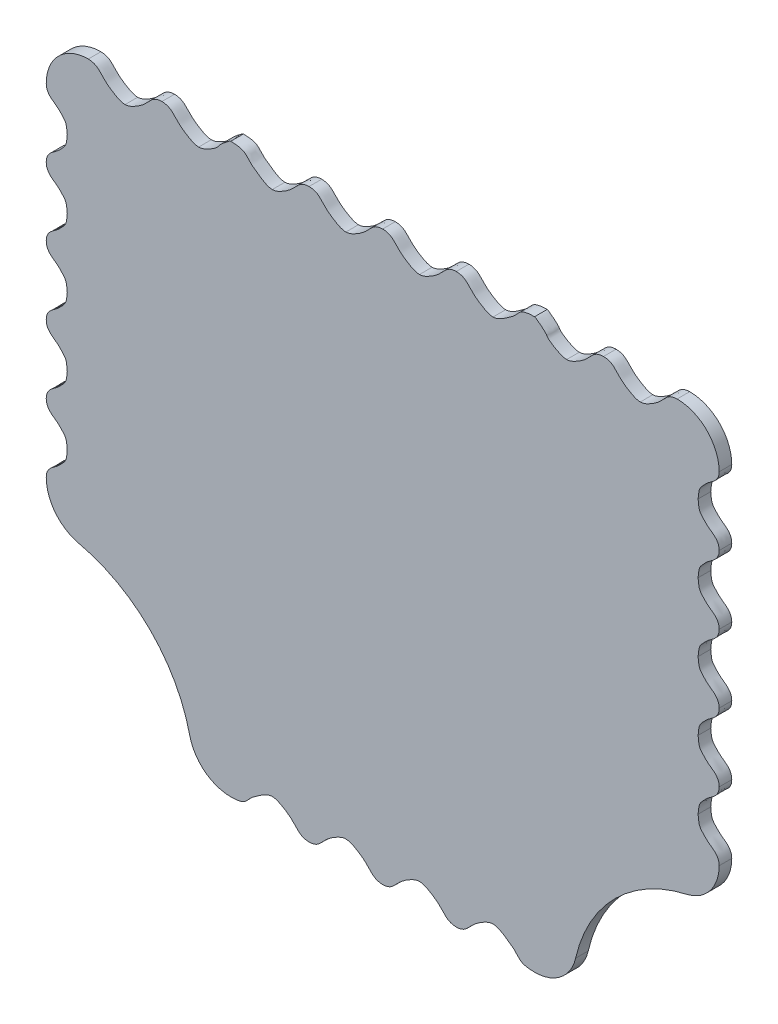
SolidWorks part; units mm, degrees
material "Beech"
ref_plane "Front" through (0, 0, 0) normal (0, 0, 1) x (1, 0, 0)
ref_plane "Top" through (0, 0, 0) normal (0, 1, 0) x (1, 0, 0)
ref_plane "Right" through (0, 0, 0) normal (1, 0, 0) x (0, 0, -1)
sketch "Sketch1" plane through (0, 0, 0) normal (0, 0, 1) x (1, 0, 0)
  line L0 (80, -32.5) -> (-80, -32.5) construction
  line L1 (-80, -67.5) -> (80, -67.5) construction
  line L2 (-80, -67.5) -> (-80, 67.5) construction
  line L3 (-80, 67.5) -> (80, 67.5) construction
  line L4 (80, -67.5) -> (80, 67.5) construction
  line L5 (-80, -67.5) -> (80, 67.5) construction
  line L6 (-80, 67.5) -> (80, -67.5) construction
  line L7 (-45, -67.5) -> (-45, 67.5) construction
  line L8 (45, -67.5) -> (45, 67.5) construction
  line L9 (80, -23.6252) -> (80, 57.5) construction
  line L10 (70, 67.5) -> (-70, 67.5) construction
  line L12 (-36.1252, -67.5) -> (36.1252, -67.5) construction
  line L13 (70, 62.5) -> (-70, 62.5) construction
  line L14 (61.25, 62.5) -> (61.25, 66.2581) construction
  line L15 (75, 57.5) -> (75, -23.6252) construction
  line L16 (0, 14.3614) -> (0, -10.6651) construction
  line L17 (75, -15.5122) -> (80, -15.5122) construction
  line L18 (-75, 57.5) -> (-75, -23.6252) construction
  line L19 (15.1664, 0) -> (-13.447, 0) construction
  arc A0 (-72.2222, -33.3751) -> (-45.8751, -59.7222) centre (-80, -67.5) cw
  arc A1 (72.2222, -33.3751) -> (45.8751, -59.7222) centre (80, -67.5) ccw
  arc A2 (-36.1252, -67.5) -> (-45.8751, -59.7222) centre (-36.1252, -57.5) cw
  arc A3 (-72.2222, -33.3751) -> (-80, -23.6252) centre (-70, -23.6252) cw
  arc A4 (45.8751, -59.7222) -> (36.1252, -67.5) centre (36.1252, -57.5) cw
  arc A5 (80, 57.5) -> (70, 67.5) centre (70, 57.5) ccw
  arc A6 (-70, 67.5) -> (-80, 57.5) centre (-70, 57.5) ccw
  arc A7 (80, -23.6252) -> (72.2222, -33.3751) centre (70, -23.6252) cw
  spline S0 degree 3 poles (70, 67.5) (68.4622, 67.4695) (66.1237, 65.2644) (66.0967, 64.9256) (62.7635, 62.457) (61.25, 62.5) knots 0 0 0 0 0.090048 0.292197 1 1 1 1
  spline S1 degree 3 poles (52.5, 67.5) (54.0378, 67.4695) (56.3763, 65.2644) (56.4033, 64.9256) (59.7365, 62.457) (61.25, 62.5) knots 0 0 0 0 0.090048 0.292197 1 1 1 1
  spline S2 degree 3 poles (52.5, 67.5) (50.9622, 67.4695) (48.6237, 65.2644) (48.5967, 64.9256) (45.2635, 62.457) (43.75, 62.5) knots 0 0 0 0 0.090048 0.292197 1 1 1 1
  spline S3 degree 3 poles (36.1252, 67.5) (36.3945, 67.4695) (39.104, 65.2644) (38.59, 64.9256) (42.2365, 62.457) (43.75, 62.5) knots 0 0 0 0 0.090048 0.292197 1 1 1 1
  spline S4 degree 3 poles (36.1252, 67.5) (33.3188, 67.4695) (31.3514, 65.2644) (30.7833, 64.9256) (27.7635, 62.457) (26.25, 62.5) knots 0 0 0 0 0.090048 0.292197 1 1 1 1
  spline S5 degree 3 poles (17.5, 67.5) (19.0378, 67.4695) (21.3763, 65.2644) (21.4033, 64.9256) (24.7365, 62.457) (26.25, 62.5) knots 0 0 0 0 0.090048 0.292197 1 1 1 1
  spline S6 degree 3 poles (17.5, 67.5) (15.9622, 67.4695) (13.6237, 65.2644) (13.5967, 64.9256) (10.2635, 62.457) (8.75, 62.5) knots 0 0 0 0 0.090048 0.292197 1 1 1 1
  spline S7 degree 3 poles (0, 67.5) (1.5378, 67.4695) (3.8763, 65.2644) (3.9033, 64.9256) (7.2365, 62.457) (8.75, 62.5) knots 0 0 0 0 0.090048 0.292197 1 1 1 1
  spline S8 degree 3 poles (0, 67.5) (-1.5378, 67.4695) (-3.8763, 65.2644) (-3.9033, 64.9256) (-7.2365, 62.457) (-8.75, 62.5) knots 0 0 0 0 0.090048 0.292197 1 1 1 1
  spline S9 degree 3 poles (-17.5, 67.5) (-15.9622, 67.4695) (-13.6237, 65.2644) (-13.5967, 64.9256) (-10.2635, 62.457) (-8.75, 62.5) knots 0 0 0 0 0.090048 0.292197 1 1 1 1
  spline S10 degree 3 poles (-17.5, 67.5) (-19.0378, 67.4695) (-21.3763, 65.2644) (-21.4033, 64.9256) (-24.7365, 62.457) (-26.25, 62.5) knots 0 0 0 0 0.090048 0.292197 1 1 1 1
  spline S11 degree 3 poles (-36.1252, 67.5) (-33.3188, 67.4695) (-31.3514, 65.2644) (-30.7833, 64.9256) (-27.7635, 62.457) (-26.25, 62.5) knots 0 0 0 0 0.090048 0.292197 1 1 1 1
  spline S12 degree 3 poles (-36.1252, 67.5) (-36.3945, 67.4695) (-39.104, 65.2644) (-38.59, 64.9256) (-42.2365, 62.457) (-43.75, 62.5) knots 0 0 0 0 0.090048 0.292197 1 1 1 1
  spline S13 degree 3 poles (-52.5, 67.5) (-50.9622, 67.4695) (-48.6237, 65.2644) (-48.5967, 64.9256) (-45.2635, 62.457) (-43.75, 62.5) knots 0 0 0 0 0.090048 0.292197 1 1 1 1
  spline S14 degree 3 poles (-52.5, 67.5) (-54.0378, 67.4695) (-56.3763, 65.2644) (-56.4033, 64.9256) (-59.7365, 62.457) (-61.25, 62.5) knots 0 0 0 0 0.090048 0.292197 1 1 1 1
  spline S15 degree 3 poles (-70, 67.5) (-68.4622, 67.4695) (-66.1237, 65.2644) (-66.0967, 64.9256) (-62.7635, 62.457) (-61.25, 62.5) knots 0 0 0 0 0.090048 0.292197 1 1 1 1
  spline S16 degree 3 poles (80, -23.6252) (80.0328, -22.0654) (78.0842, -20.4866) (77.3009, -20.0392) (75.2934, -17.9415) (75.1919, -17.7457) (75, -15.5122) knots 0 0 0 0 0.224601 0.419775 0.497315 1 1 1 1
  spline S17 degree 3 poles (80, -7.3992) (80.0328, -8.959) (78.0842, -10.5377) (77.3009, -10.9851) (75.2934, -13.0829) (75.1919, -13.2787) (75, -15.5122) knots 0 0 0 0 0.224601 0.419775 0.497315 1 1 1 1
  spline S18 degree 3 poles (80, -7.3992) (80.0328, -5.8394) (78.0842, -4.255) (77.3009, -3.8094) (75.2934, -1.7111) (75.1919, -1.5157) (75, 0.7178) knots 0 0 0 0 0.224601 0.419775 0.497315 1 1 1 1
  spline S19 degree 3 poles (80, 8.8308) (80.0328, 7.271) (78.0842, 5.6923) (77.3009, 5.2449) (75.2934, 3.1471) (75.1919, 2.9513) (75, 0.7178) knots 0 0 0 0 0.224601 0.419775 0.497315 1 1 1 1
  spline S20 degree 3 poles (80, 8.8308) (80.0328, 10.3906) (78.0842, 11.975) (77.3009, 12.4206) (75.2934, 14.5189) (75.1919, 14.7143) (75, 16.9478) knots 0 0 0 0 0.224601 0.419775 0.497315 1 1 1 1
  spline S21 degree 3 poles (80, 25.0608) (80.0328, 23.501) (78.0842, 21.9223) (77.3009, 21.4749) (75.2934, 19.3771) (75.1919, 19.1813) (75, 16.9478) knots 0 0 0 0 0.224601 0.419775 0.497315 1 1 1 1
  spline S22 degree 3 poles (80, 25.0608) (80.0328, 26.6206) (78.0842, 28.205) (77.3009, 28.6506) (75.2934, 30.7489) (75.1919, 30.9443) (75, 33.1778) knots 0 0 0 0 0.224601 0.419775 0.497315 1 1 1 1
  spline S23 degree 3 poles (80, 41.2908) (80.0328, 39.731) (78.0842, 38.1523) (77.3009, 37.7049) (75.2934, 35.6071) (75.1919, 35.4113) (75, 33.1778) knots 0 0 0 0 0.224601 0.419775 0.497315 1 1 1 1
  spline S24 degree 3 poles (80, 57.5) (80.0328, 55.9402) (78.0842, 54.3853) (77.3009, 53.9302) (75.2934, 51.8346) (75.1919, 51.6373) (75, 49.4038) knots 0 0 0 0 0.224601 0.419775 0.497315 1 1 1 1
  spline S25 degree 3 poles (80, 41.2908) (80.0328, 42.8506) (78.0842, 44.4294) (77.3009, 44.8768) (75.2934, 46.9745) (75.1919, 47.1703) (75, 49.4038) knots 0 0 0 0 0.224601 0.419775 0.497315 1 1 1 1
  spline S26 degree 3 poles (-80, 41.2908) (-80.0328, 42.8506) (-78.0842, 44.4294) (-77.3009, 44.8768) (-75.2934, 46.9745) (-75.1919, 47.1703) (-75, 49.4038) knots 0 0 0 0 0.224601 0.419775 0.497315 1 1 1 1
  spline S27 degree 3 poles (-80, 57.5) (-80.0328, 55.9402) (-78.0842, 54.3853) (-77.3009, 53.9302) (-75.2934, 51.8346) (-75.1919, 51.6373) (-75, 49.4038) knots 0 0 0 0 0.224601 0.419775 0.497315 1 1 1 1
  spline S28 degree 3 poles (-80, 41.2908) (-80.0328, 39.731) (-78.0842, 38.1523) (-77.3009, 37.7049) (-75.2934, 35.6071) (-75.1919, 35.4113) (-75, 33.1778) knots 0 0 0 0 0.224601 0.419775 0.497315 1 1 1 1
  spline S29 degree 3 poles (-80, 25.0608) (-80.0328, 26.6206) (-78.0842, 28.205) (-77.3009, 28.6506) (-75.2934, 30.7489) (-75.1919, 30.9443) (-75, 33.1778) knots 0 0 0 0 0.224601 0.419775 0.497315 1 1 1 1
  spline S30 degree 3 poles (-80, 25.0608) (-80.0328, 23.501) (-78.0842, 21.9223) (-77.3009, 21.4749) (-75.2934, 19.3771) (-75.1919, 19.1813) (-75, 16.9478) knots 0 0 0 0 0.224601 0.419775 0.497315 1 1 1 1
  spline S31 degree 3 poles (-80, 8.8308) (-80.0328, 10.3906) (-78.0842, 11.975) (-77.3009, 12.4206) (-75.2934, 14.5189) (-75.1919, 14.7143) (-75, 16.9478) knots 0 0 0 0 0.224601 0.419775 0.497315 1 1 1 1
  spline S32 degree 3 poles (-80, 8.8308) (-80.0328, 7.271) (-78.0842, 5.6923) (-77.3009, 5.2449) (-75.2934, 3.1471) (-75.1919, 2.9513) (-75, 0.7178) knots 0 0 0 0 0.224601 0.419775 0.497315 1 1 1 1
  spline S33 degree 3 poles (-80, -7.3992) (-80.0328, -5.8394) (-78.0842, -4.255) (-77.3009, -3.8094) (-75.2934, -1.7111) (-75.1919, -1.5157) (-75, 0.7178) knots 0 0 0 0 0.224601 0.419775 0.497315 1 1 1 1
  spline S34 degree 3 poles (-80, -7.3992) (-80.0328, -8.959) (-78.0842, -10.5377) (-77.3009, -10.9851) (-75.2934, -13.0829) (-75.1919, -13.2787) (-75, -15.5122) knots 0 0 0 0 0.224601 0.419775 0.497315 1 1 1 1
  spline S35 degree 3 poles (-80, -23.6252) (-80.0328, -22.0654) (-78.0842, -20.4866) (-77.3009, -20.0392) (-75.2934, -17.9415) (-75.1919, -17.7457) (-75, -15.5122) knots 0 0 0 0 0.224601 0.419775 0.497315 1 1 1 1
  spline S36 degree 3 poles (36.1252, -67.5) (33.3188, -67.4695) (31.3514, -65.2644) (30.7833, -64.9256) (27.7635, -62.457) (26.25, -62.5) knots 0 0 0 0 0.090048 0.292197 1 1 1 1
  spline S37 degree 3 poles (-36.1252, -67.5) (-33.3188, -67.4695) (-31.3514, -65.2644) (-30.7833, -64.9256) (-27.7635, -62.457) (-26.25, -62.5) knots 0 0 0 0 0.090048 0.292197 1 1 1 1
  spline S38 degree 3 poles (-17.5, -67.5) (-19.0378, -67.4695) (-21.3763, -65.2644) (-21.4033, -64.9256) (-24.7365, -62.457) (-26.25, -62.5) knots 0 0 0 0 0.090048 0.292197 1 1 1 1
  spline S39 degree 3 poles (-17.5, -67.5) (-15.9622, -67.4695) (-13.6237, -65.2644) (-13.5967, -64.9256) (-10.2635, -62.457) (-8.75, -62.5) knots 0 0 0 0 0.090048 0.292197 1 1 1 1
  spline S40 degree 3 poles (0, -67.5) (-1.5378, -67.4695) (-3.8763, -65.2644) (-3.9033, -64.9256) (-7.2365, -62.457) (-8.75, -62.5) knots 0 0 0 0 0.090048 0.292197 1 1 1 1
  spline S41 degree 3 poles (0, -67.5) (1.5378, -67.4695) (3.8763, -65.2644) (3.9033, -64.9256) (7.2365, -62.457) (8.75, -62.5) knots 0 0 0 0 0.090048 0.292197 1 1 1 1
  spline S42 degree 3 poles (17.5, -67.5) (15.9622, -67.4695) (13.6237, -65.2644) (13.5967, -64.9256) (10.2635, -62.457) (8.75, -62.5) knots 0 0 0 0 0.090048 0.292197 1 1 1 1
  spline S43 degree 3 poles (17.5, -67.5) (19.0378, -67.4695) (21.3763, -65.2644) (21.4033, -64.9256) (24.7365, -62.457) (26.25, -62.5) knots 0 0 0 0 0.090048 0.292197 1 1 1 1
  point P0 (0, 0)
  point P14 (0, 0)
  point P45 (0, 0)
  point P82 (0, 0)
  point P94 (0, 0)
  point P107 (0, 0)
  point P178 (0, 0)
  point P179 (36.1298, -67.5)
  point P180 (36.1252, -67.5)
  point P181 (0, 0)
  dimension "D6" = 10
  dimension "D7" = 10
  dimension "D8" = 10
  dimension "D11" = 5
  dimension "D1" = 135
  dimension "D2" = 160
  dimension "D3" = 35
  dimension "D4" = 35
  dimension "D5" = 35
  dimension "D10" = 8.75
  dimension "D12" = 5
  dimension "D13" = 8.113
extrude "Boss-Extrude1" add sketch "Sketch1" along normal blind 3
